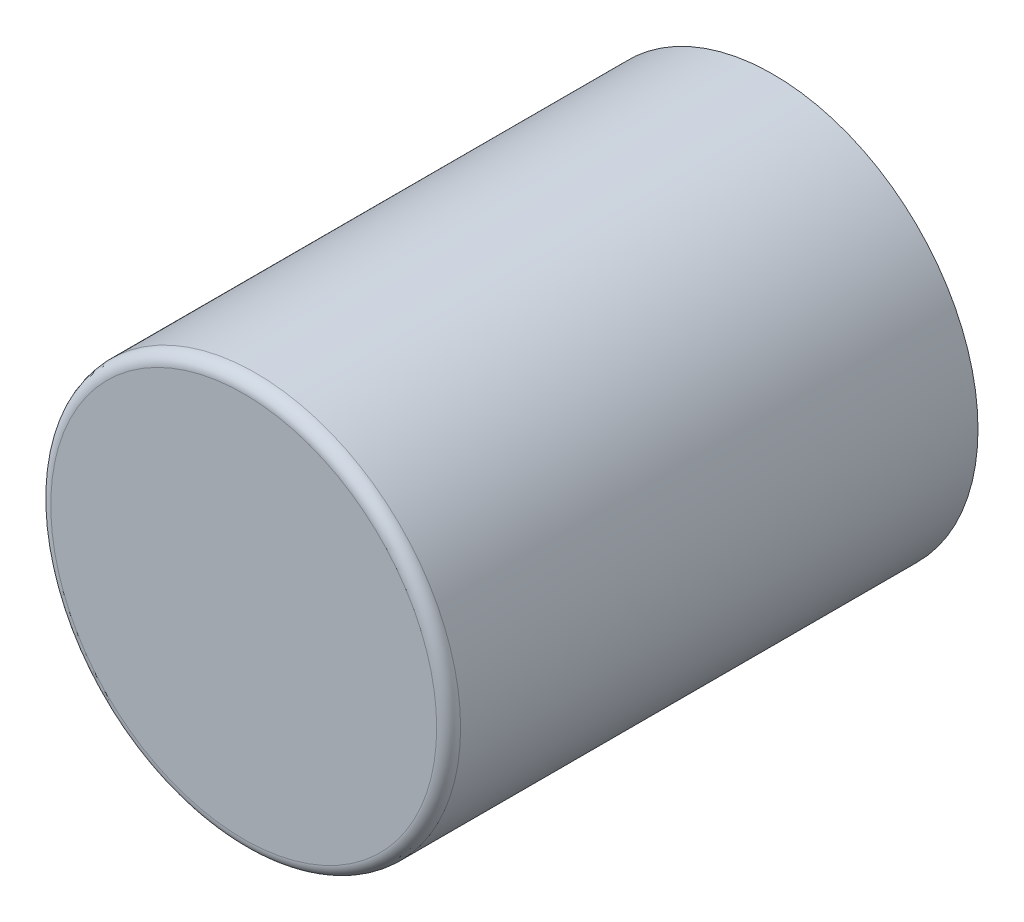
SolidWorks part; units mm, degrees
ref_plane "Alzado" through (0, 0, 0) normal (0, 0, 1) x (1, 0, 0)
ref_plane "Planta" through (0, 0, 0) normal (0, 1, 0) x (1, 0, 0)
ref_plane "Vista lateral" through (0, 0, 0) normal (1, 0, 0) x (0, 0, -1)
sketch "Croquis1" plane through (0, 0, 0) normal (0, 0, 1) x (1, 0, 0)
  circle A0 centre (0, 0) radius 12
  dimension "D1" = 24
extrude "Saliente-Extruir1" add sketch "Croquis1" along normal blind 31
fillet "Redondeo2" radius 0.7 1 edges at (12, 0, 31)
